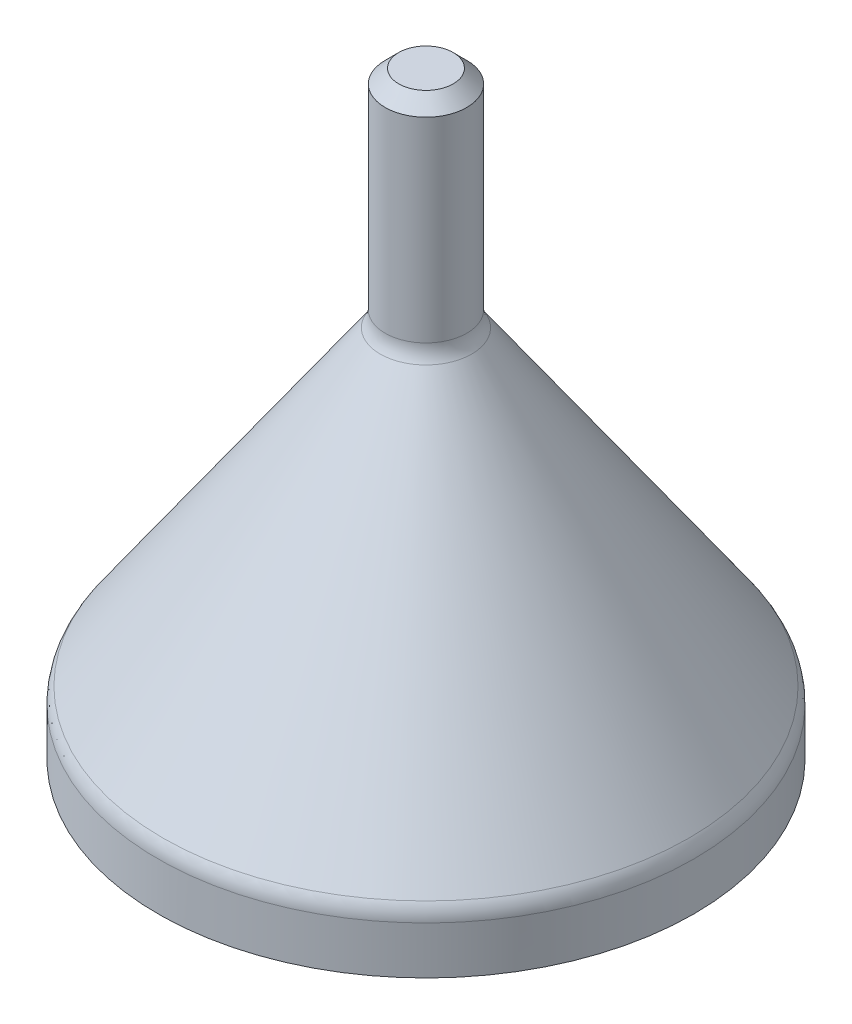
SolidWorks part; units mm, degrees
ref_plane "Front Plane" through (0, 0, 0) normal (0, 0, 1) x (1, 0, 0)
ref_plane "Top Plane" through (0, 0, 0) normal (0, 1, 0) x (1, 0, 0)
ref_plane "Right Plane" through (0, 0, 0) normal (1, 0, 0) x (0, 0, -1)
sketch "Sketch1" plane through (0, 0, 0) normal (0, 0, 1) x (1, 0, 0)
  line L0 (0, 0) -> (0, 28.7782) construction
  line L1 (17.7, 0) -> (17.7, 3.5)
  line L2 (17.7, 3.5) -> (0, 28.7782)
  line L3 (17.7, 0) -> (19.7, 0)
  line L4 (19.7, 0) -> (19.7, 4.1306)
  line L5 (19.7, 4.1306) -> (3, 27.9807)
  line L6 (3, 27.9807) -> (3, 43.9807)
  line L7 (3, 43.9807) -> (0, 43.9807)
  line L8 (0, 43.9807) -> (0, 28.7782)
  point P5 (1.5, 43.9807)
  dimension "D1" = 17.7
  dimension "D2" = 2
  dimension "D3" = 2
  dimension "D4" = 3.5
  dimension "D5" = 3
  dimension "D6" = 145
  dimension "D7" = 16
revolve "Revolve1" add sketch "Sketch1" angle 360 about L0
fillet "Fillet1" radius 2 2 edges at (3, 27.9807, 0) (19.7, 4.1306, 0)
sketch "Sketch2" plane through (0, 0, 0) normal (1, 0, 0) x (0, 0, -1)
  circle A0 centre (0, 12) radius 1.5
  point P2 (0, 0)
  dimension "D1" = 3
  dimension "D2" = 12
extrude "Boss-Extrude1" add sketch "Sketch2" along normal up to next and the other way up to next
chamfer "Chamfer1" distance 1 angle 45 1 edges at (3, 43.9807, 0)
sketch "Sketch3" plane through (0, 0, 0) normal (0, -1, 0) x (1, 0, 0)
  line L0 (0, 19.7) -> (0, -19.7) construction
  line L1 (-3.2, 18.6271) -> (-3.2, 17.4083)
  line L2 (3.2, 18.6271) -> (3.2, 17.4083)
  line L3 (-3.2, 19.7) -> (-3.2, -19.7) construction
  line L4 (3.2, 19.7) -> (3.2, -19.7) construction
  line L5 (3.2, -17.4083) -> (3.2, -18.6271)
  line L6 (-3.2, -17.4083) -> (-3.2, -18.6271)
  circle A0 centre (0, 0) radius 19.7 construction
  circle A3 centre (0, 0) radius 18.9
  arc A4 (-3.2, -18.6271) -> (3.2, -18.6271) centre (0, 0) ccw
  circle A5 centre (0, 0) radius 17.7 construction
  arc A6 (-3.2, -17.4083) -> (3.2, -17.4083) centre (0, 0) ccw
  arc A7 (3.2, 18.6271) -> (-3.2, 18.6271) centre (0, 0) ccw
  arc A8 (3.2, 17.4083) -> (-3.2, 17.4083) centre (0, 0) ccw
  dimension "D1" = 1.2
  dimension "D2" = 3.2
  dimension "D3" = 3.2
extrude "Cut-Extrude1" cut sketch "Sketch3" against normal blind 3
